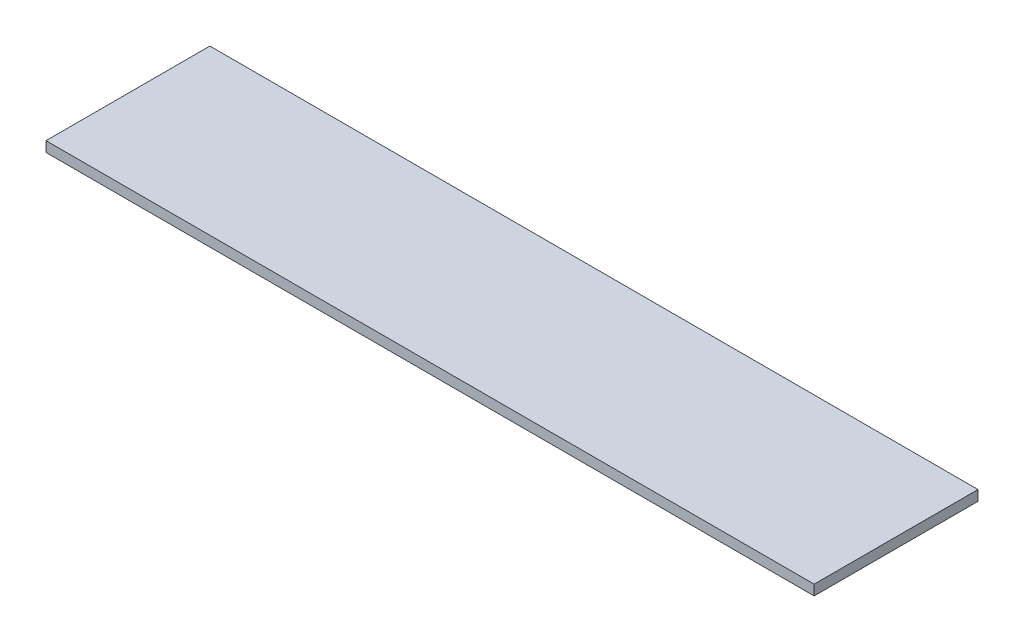
SolidWorks part; units mm, degrees
ref_plane "Front Plane" through (0, 0, 0) normal (0, 0, 1) x (1, 0, 0)
ref_plane "Top Plane" through (0, 0, 0) normal (0, 1, 0) x (1, 0, 0)
ref_plane "Right Plane" through (0, 0, 0) normal (1, 0, 0) x (0, 0, -1)
sketch "Sketch1" plane through (0, 0, 0) normal (0, 1, 0) x (1, 0, 0)
  line L0 (0, 0) -> (150, 0)
  line L1 (150, 0) -> (150, 32)
  line L2 (150, 32) -> (0, 32)
  line L3 (0, 32) -> (0, 0)
  dimension "D1" = 150
  dimension "D2" = 32
extrude "Boss-Extrude1" add sketch "Sketch1" along normal blind 2
